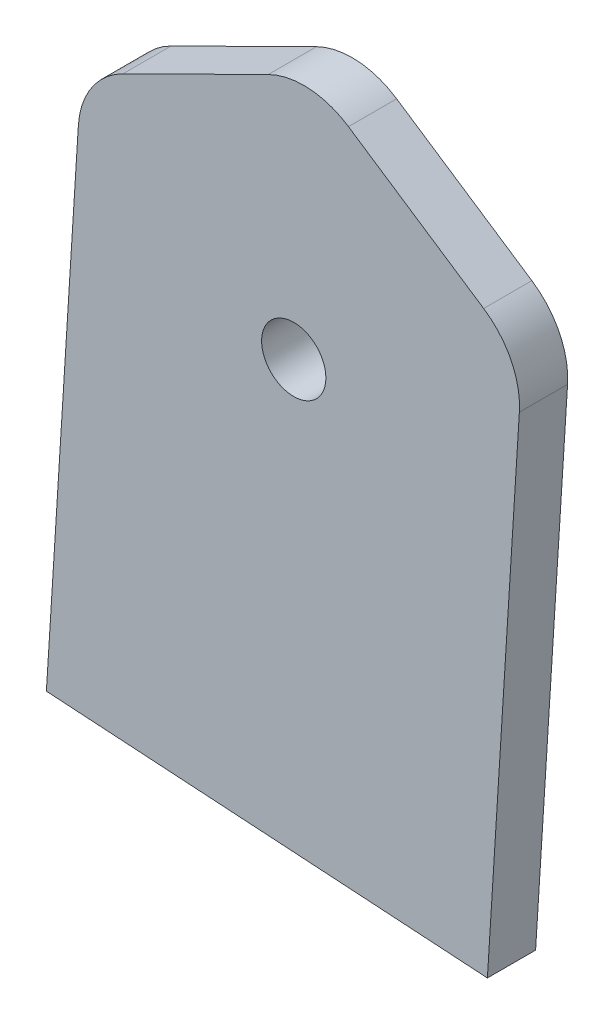
SolidWorks part; units mm, degrees
ref_plane "Front Plane" through (0, 0, 0) normal (0, 0, 1) x (1, 0, 0)
ref_plane "Top Plane" through (0, 0, 0) normal (0, 1, 0) x (1, 0, 0)
ref_plane "Right Plane" through (0, 0, 0) normal (1, 0, 0) x (0, 0, -1)
sketch "Sketch1" plane through (0, 0, 0) normal (0, 0, 1) x (1, 0, 0)
  line L0 (-175.7132, 296.792) -> (-157.6108, 305.7717)
  line L1 (-147.6307, 305.141) -> (-130.8029, 293.9537)
  line L5 (-185.2295, 225.4867) -> (-130.3391, 222.0177)
  line L6 (-130.3391, 222.0177) -> (-126.3591, 284.9954)
  line L9 (-181.2494, 288.4643) -> (-185.2295, 225.4867)
  arc A0 (-181.2494, 288.4643) -> (-175.7132, 296.792) centre (-171.2694, 287.8336) cw
  arc A1 (-157.6108, 305.7717) -> (-147.6307, 305.141) centre (-153.167, 296.8133) cw
  arc A2 (-130.8029, 293.9537) -> (-126.3591, 284.9954) centre (-136.3391, 285.6261) cw
  circle A3 centre (-154.4417, 276.6436) radius 4
  point P12 (0, 0)
  point P13 (-152.5363, 306.7934)
  dimension "D3" = 10
  dimension "D4" = 60
  dimension "D8" = 8
  dimension "D1" = 63.1033
  dimension "D2" = 54.9999
  dimension "D5" = 60
  dimension "D6" = 60
  dimension "D7" = 30.21
  dimension "D9" = 27.5
  dimension "D10" = 222.0177
  dimension "D11" = 130.3391
  dimension "D12" = 213.3548
extrude "Boss-Extrude1" add sketch "Sketch1" along normal blind 6 separate body
